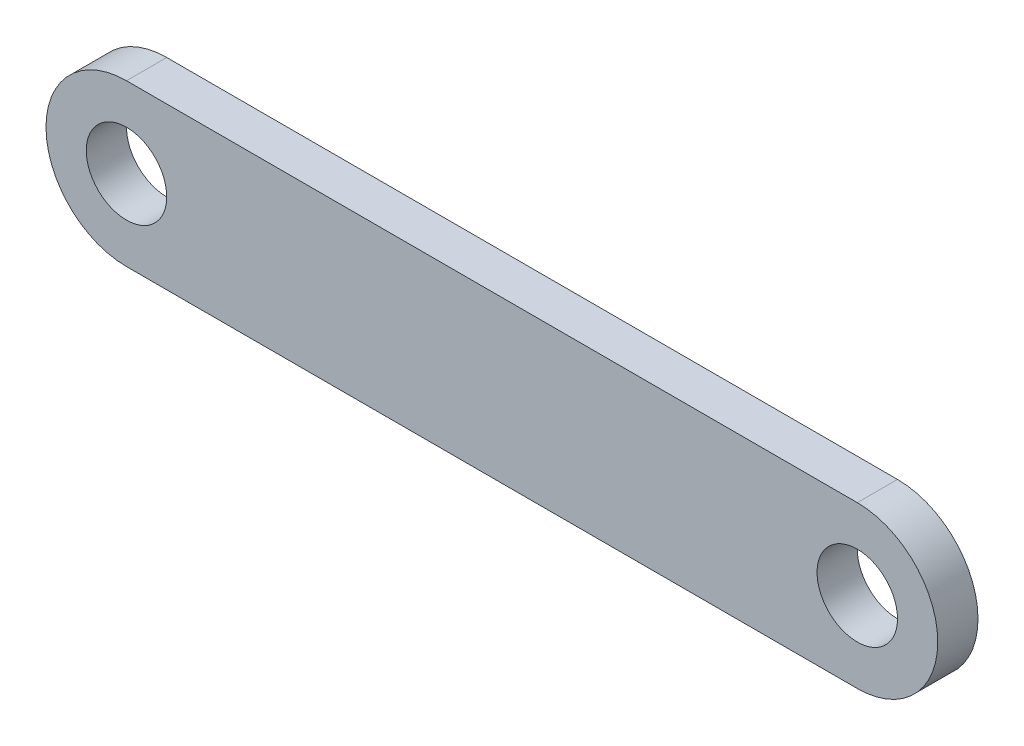
SolidWorks part; units mm, degrees
ref_plane "Спереди" through (0, 0, 0) normal (0, 0, 1) x (1, 0, 0)
ref_plane "Сверху" through (0, 0, 0) normal (0, 1, 0) x (1, 0, 0)
ref_plane "Справа" through (0, 0, 0) normal (1, 0, 0) x (0, 0, -1)
sketch "Sketch1" plane through (0, 0, 0) normal (0, 0, 1) x (1, 0, 0)
  line L0 (0, 0) -> (18.16, 0)
  line L1 (0, 2) -> (18.16, 2)
  line L2 (0, -2) -> (18.16, -2)
  circle A0 centre (0, 0) radius 1
  circle A1 centre (18.16, 0) radius 1
  circle A2 centre (0, 0) radius 2
  circle A3 centre (18.16, 0) radius 2
  dimension "D1" = 18.16
extrude "Extrude1" add sketch "Sketch1" against normal blind 1
